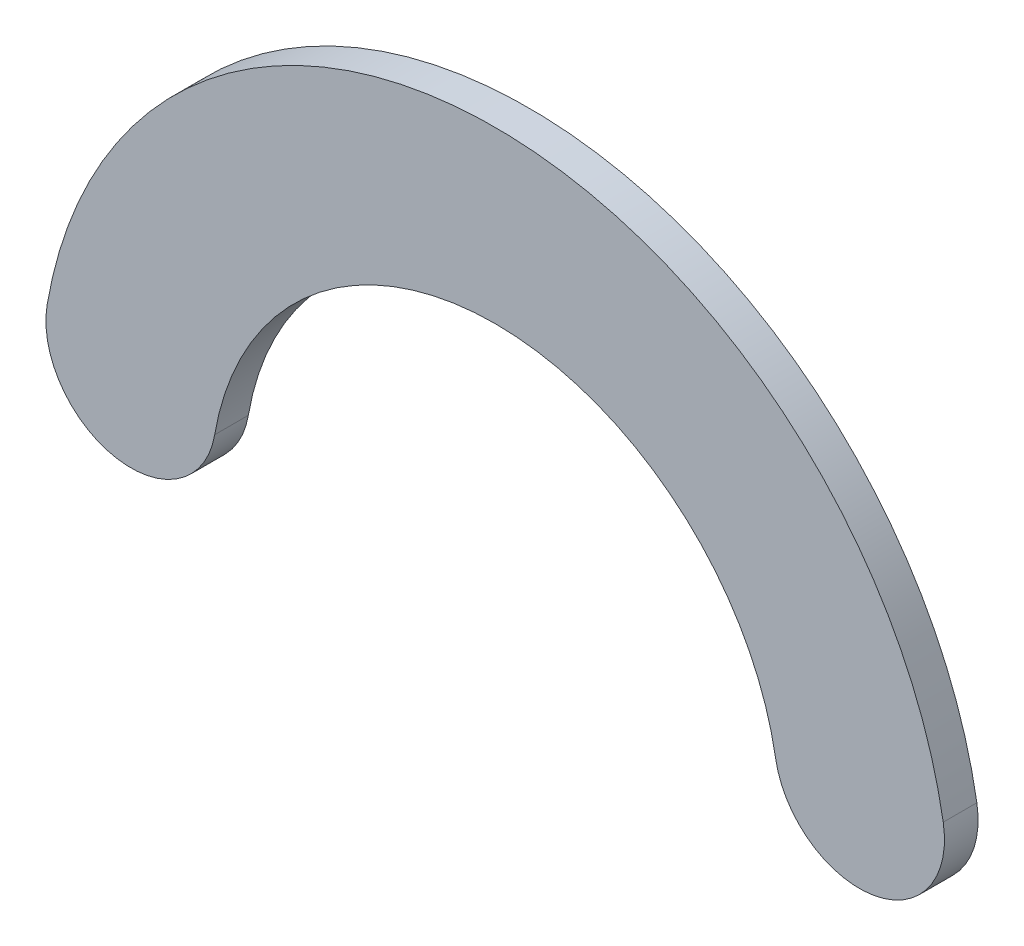
SolidWorks part; units mm, degrees
ref_plane "Front Plane" through (0, 0, 0) normal (0, 0, 1) x (1, 0, 0)
ref_plane "Top Plane" through (0, 0, 0) normal (0, 1, 0) x (1, 0, 0)
ref_plane "Right Plane" through (0, 0, 0) normal (1, 0, 0) x (0, 0, -1)
sketch "Sketch1" plane through (0, 0, 0) normal (0, 0, 1) x (1, 0, 0)
  arc A0 (-37.3849, 12.3321) -> (70.9227, 12.3321) centre (16.7689, 3.0412) cw construction
  arc A1 (83.3785, 14.469) -> (-49.8407, 14.469) centre (16.7689, 3.0412) ccw
  arc A2 (58.467, 10.1951) -> (-24.9292, 10.1951) centre (16.7689, 3.0412) ccw
  arc A3 (58.467, 10.1951) -> (83.3785, 14.469) centre (70.9227, 12.3321) ccw
  arc A4 (-49.8407, 14.469) -> (-24.9292, 10.1951) centre (-37.3849, 12.3321) ccw
  point P3 (16.7689, 57.9863)
extrude "Boss-Extrude1" add sketch "Sketch1" along normal blind 5
sketch "Sketch2" plane through (0, 0, 0) normal (0, 0, -1) x (-1, 0, 0)
  arc A0 (-70.9227, 12.3321) -> (37.3849, 12.3321) centre (-16.7689, 3.8078) cw construction
  arc A1 (46.9494, 13.8376) -> (-80.4872, 13.8376) centre (-16.7689, 3.8078) ccw
  arc A2 (27.8204, 10.8265) -> (-61.3582, 10.8265) centre (-16.7689, 3.8078) ccw
  arc A3 (27.8204, 10.8265) -> (46.9494, 13.8376) centre (37.3849, 12.3321) ccw
  arc A4 (-80.4872, 13.8376) -> (-61.3582, 10.8265) centre (-70.9227, 12.3321) ccw
  point P3 (-16.7689, 58.6284)
extrude "Cut-Extrude1" cut sketch "Sketch2" against normal blind 3.5
